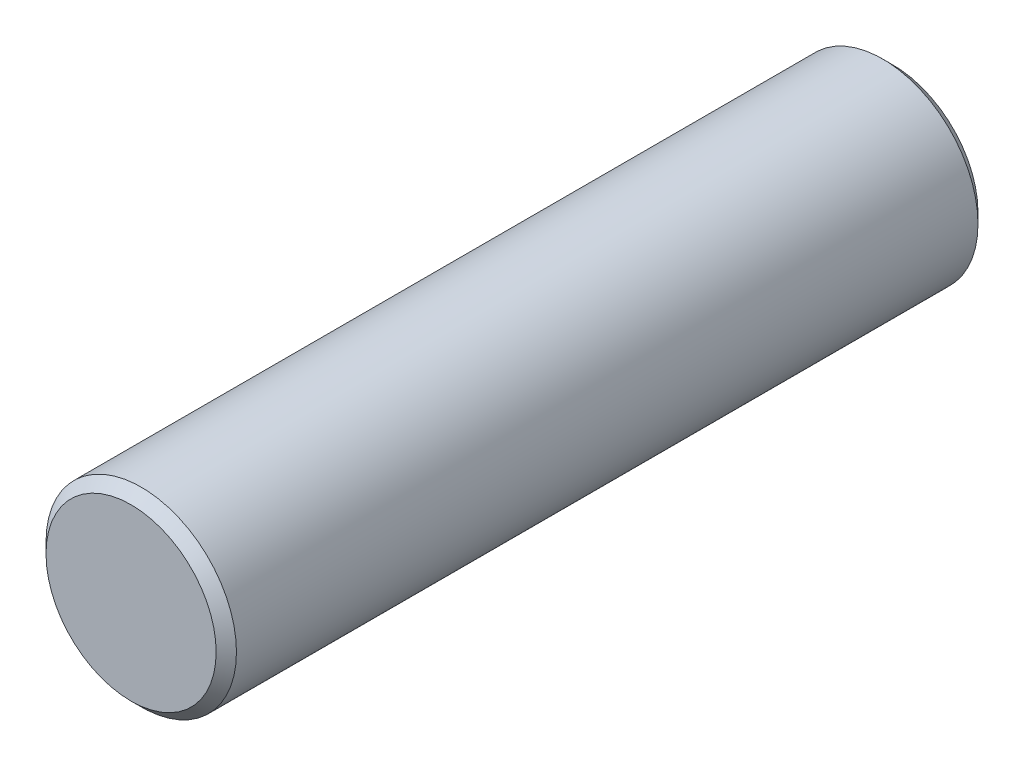
SolidWorks part; units mm, degrees
ref_plane "Front Plane" through (0, 0, 0) normal (0, 0, 1) x (1, 0, 0)
ref_plane "Top Plane" through (0, 0, 0) normal (0, 1, 0) x (1, 0, 0)
ref_plane "Right Plane" through (0, 0, 0) normal (1, 0, 0) x (0, 0, -1)
sketch "Sketch1" plane through (0, 0, 0) normal (0, 0, 1) x (1, 0, 0)
  circle A0 centre (0, 0) radius 4.7625
  dimension "D1" = 9.525
extrude "Boss-Extrude1" add sketch "Sketch1" along normal blind 38.1 contours A0
chamfer "Chamfer1" distance 0.508 angle 45 2 edges at (4.7625, 0, 0) (4.7625, 0, 38.1)
